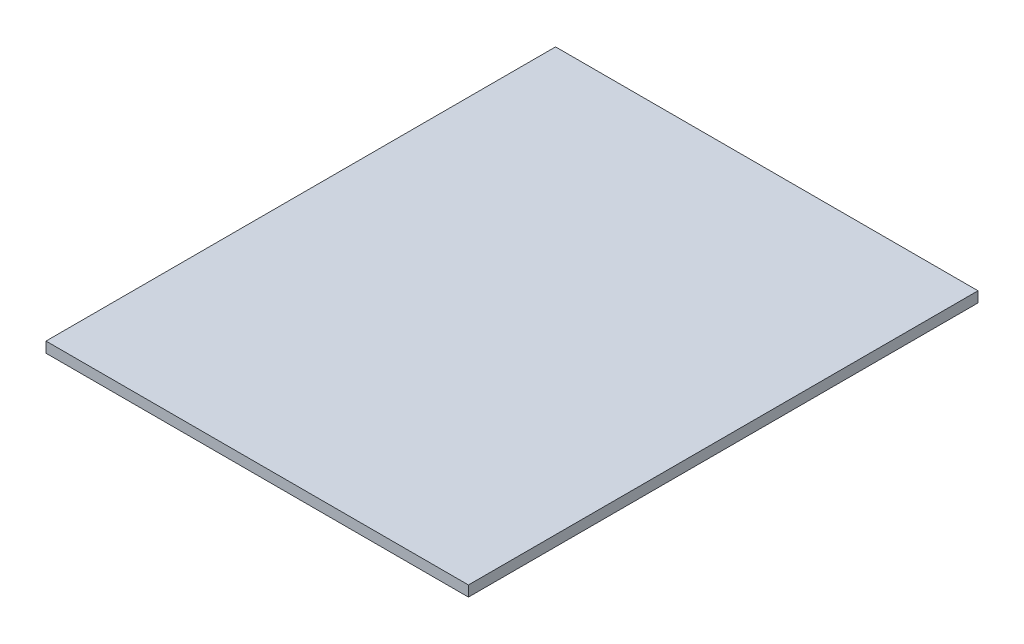
SolidWorks part; units mm, degrees
material "橡木"
ref_plane "前视基准面" through (0, 0, 0) normal (0, 0, 1) x (1, 0, 0)
ref_plane "上视基准面" through (0, 0, 0) normal (0, 1, 0) x (1, 0, 0)
ref_plane "右视基准面" through (0, 0, 0) normal (1, 0, 0) x (0, 0, -1)
other "Configuration Table"
sketch "草图1" plane through (0, 0, 0) normal (0, 1, 0) x (1, 0, 0)
  line L1 (0, 0) -> (800, 0)
  line L2 (0, 0) -> (0, 965)
  line L3 (0, 965) -> (800, 965)
  line L4 (800, 0) -> (800, 965)
  dimension "D1" = 800
  dimension "D2" = 965
extrude "凸台-拉伸1" add sketch "草图1" along normal blind 20
